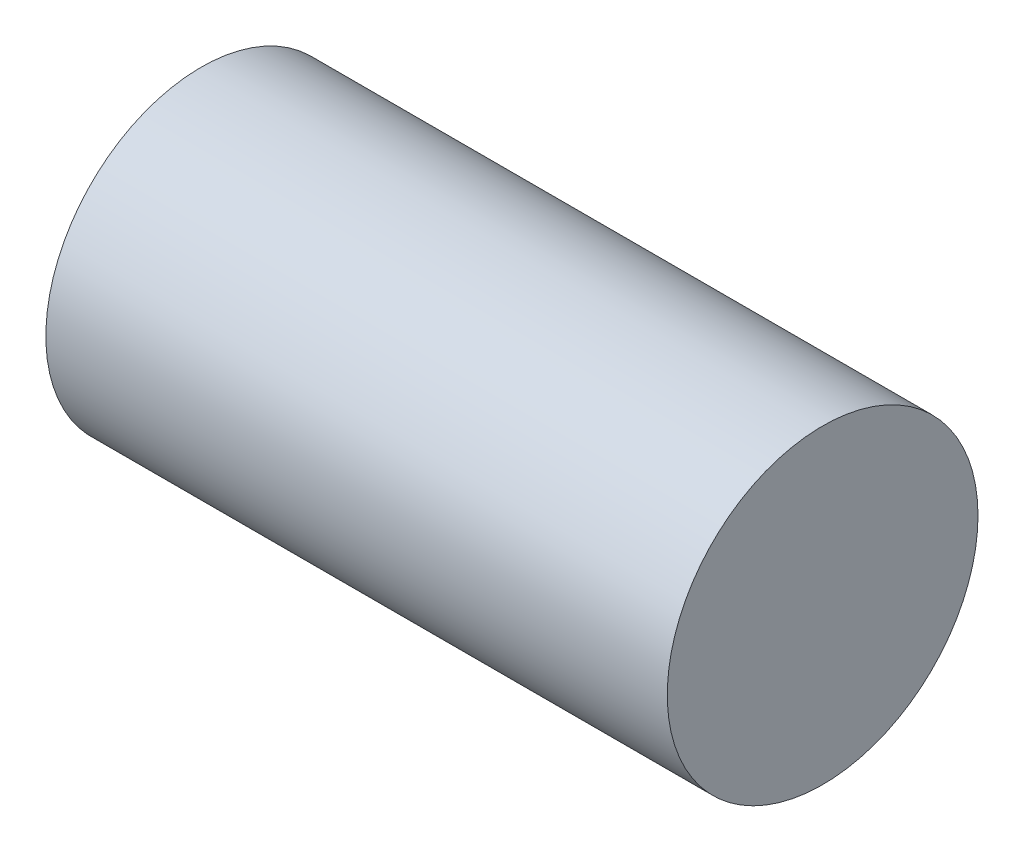
SolidWorks part; units mm, degrees
ref_plane "Front Plane" through (0, 0, 0) normal (0, 0, 1) x (1, 0, 0)
ref_plane "Top Plane" through (0, 0, 0) normal (0, 1, 0) x (1, 0, 0)
ref_plane "Right Plane" through (0, 0, 0) normal (1, 0, 0) x (0, 0, -1)
sketch "Sketch1" plane through (0, 0, 0) normal (1, 0, 0) x (0, 0, -1)
  circle A0 centre (0, 0) radius 6.35
  dimension "D1" = 12.7
extrude "Boss-Extrude1" add sketch "Sketch1" along normal blind 25.4
